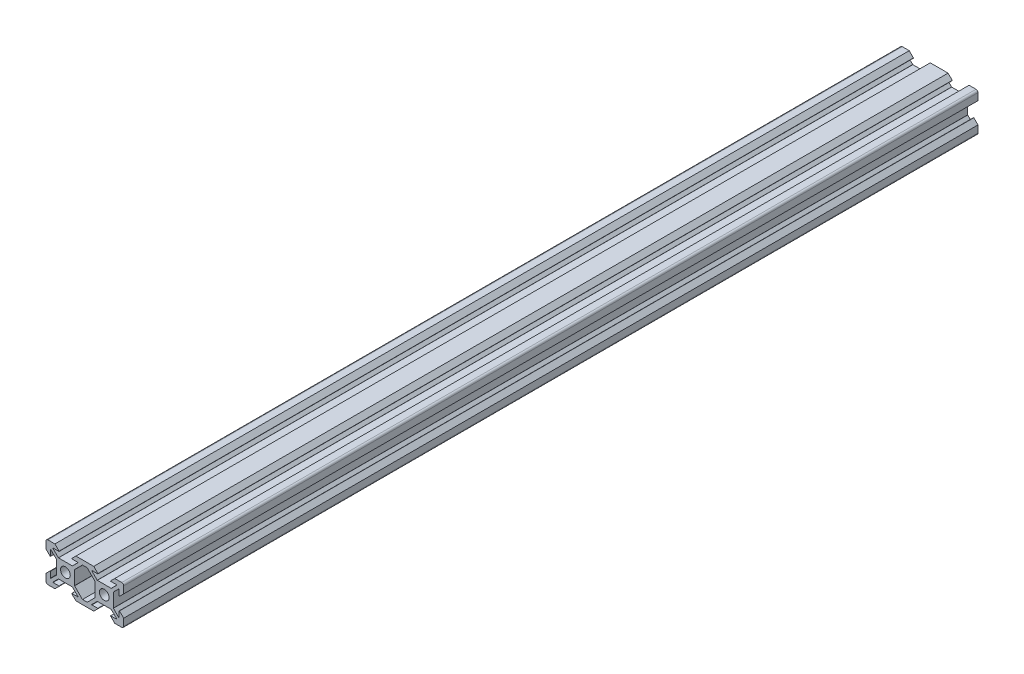
SolidWorks part; units mm, degrees
ref_plane "Alzado" through (0, 0, 0) normal (0, 0, 1) x (1, 0, 0)
ref_plane "Planta" through (0, 0, 0) normal (0, 1, 0) x (1, 0, 0)
ref_plane "Vista lateral" through (0, 0, 0) normal (1, 0, 0) x (0, 0, -1)
sketch "Croquis1" plane through (0, 0, 0) normal (0, 1, 0) x (1, 0, 0)
  line L0 (0, 220) -> (0, -220)
  dimension "D1" = 440
other "Miembro estructural1"
ref_plane "Plano1" through (0, 0, -220) normal (0, 0, 1) x (1, 0, 0)
sketch "Croquis4" plane through (0, 0, -220) normal (0, 0, 1) x (1, 0, 0)
  line L0 (0, 10) -> (0, 7.6897) construction
  line L1 (-19, -10) -> (-15.4103, -10)
  line L2 (-20, -9) -> (-20, -5.4103)
  line L3 (-19, 10) -> (-15.4103, 10)
  line L5 (20, 5.4103) -> (20, 9)
  line L6 (20, 5.4103) -> (17.8604, 3.2707)
  line L8 (17.6897, 3.3414) -> (17.6897, 6.3586)
  line L9 (-15.4103, 10) -> (-13.2707, 7.8604)
  line L10 (-13.3414, 7.6897) -> (-16.3586, 7.6897)
  line L11 (-16.4293, 7.519) -> (-13.6293, 4.719)
  line L12 (-13.5586, 4.6897) -> (-6.4414, 4.6897)
  line L13 (-3.5707, 7.519) -> (-6.3707, 4.719)
  line L14 (-6.6586, 7.6897) -> (-3.6414, 7.6897)
  line L15 (-4.5897, 10) -> (-6.7293, 7.8604)
  line L16 (-4.5897, 10) -> (4.5897, 10)
  line L17 (17.519, 6.4293) -> (14.719, 3.6293)
  line L18 (14.6897, -3.5586) -> (14.6897, 3.5586)
  line L19 (-2.481, 6.4293) -> (-5.281, 3.6293)
  line L20 (-5.3103, 3.5586) -> (-5.3103, -3.5586)
  line L21 (-2.481, -6.4293) -> (-5.281, -3.6293)
  line L22 (17.519, -6.4293) -> (14.719, -3.6293)
  line L23 (17.6897, -3.3414) -> (17.6897, -6.3586)
  line L24 (-4.5897, -10) -> (-6.7293, -7.8604)
  line L25 (-6.6586, -7.6897) -> (-3.6414, -7.6897)
  line L26 (-3.5707, -7.519) -> (-6.3707, -4.719)
  line L27 (-6.4414, -4.6897) -> (-13.5586, -4.6897)
  line L28 (-16.4293, -7.519) -> (-13.6293, -4.719)
  line L29 (-13.3414, -7.6897) -> (-16.3586, -7.6897)
  line L30 (-15.4103, -10) -> (-13.2707, -7.8604)
  line L31 (-20, -5.4103) -> (-17.8604, -3.2707)
  line L32 (-17.6897, -3.3414) -> (-17.6897, -6.3586)
  line L33 (-17.519, -6.4293) -> (-14.719, -3.6293)
  line L34 (-14.6897, -3.5586) -> (-14.6897, 3.5586)
  line L35 (-17.519, 6.4293) -> (-14.719, 3.6293)
  line L36 (-17.6897, 3.3414) -> (-17.6897, 6.3586)
  line L37 (-20, 5.4103) -> (-17.8604, 3.2707)
  line L38 (-20, 5.4103) -> (-20, 9)
  line L39 (-4.5897, -10) -> (4.5897, -10)
  line L40 (-2.3103, 3.3414) -> (-2.3103, 6.3586) [skipped]
  line L41 (0, 5.4103) -> (-2.1396, 3.2707) [skipped]
  line L42 (-2.3103, -3.3414) -> (-2.3103, -6.3586) [skipped]
  line L43 (0, -5.4103) -> (-2.1396, -3.2707) [skipped]
  line L44 (20, -5.4103) -> (17.8604, -3.2707)
  line L45 (15.4103, -10) -> (13.2707, -7.8604)
  line L46 (13.3414, -7.6897) -> (16.3586, -7.6897)
  line L47 (16.4293, -7.519) -> (13.6293, -4.719)
  line L48 (6.4414, -4.6897) -> (13.5586, -4.6897)
  line L49 (3.5707, -7.519) -> (6.3707, -4.719)
  line L50 (6.6586, -7.6897) -> (3.6414, -7.6897)
  line L51 (4.5897, -10) -> (6.7293, -7.8604)
  line L52 (2.481, -6.4293) -> (5.281, -3.6293)
  line L53 (5.3103, 3.5586) -> (5.3103, -3.5586)
  line L54 (2.481, 6.4293) -> (5.281, 3.6293)
  line L55 (4.5897, 10) -> (6.7293, 7.8604)
  line L56 (6.6586, 7.6897) -> (3.6414, 7.6897)
  line L57 (3.5707, 7.519) -> (6.3707, 4.719)
  line L58 (13.5586, 4.6897) -> (6.4414, 4.6897)
  line L59 (16.4293, 7.519) -> (13.6293, 4.719)
  line L60 (13.3414, 7.6897) -> (16.3586, 7.6897)
  line L61 (15.4103, 10) -> (13.2707, 7.8604)
  line L62 (19, 10) -> (15.4103, 10)
  line L63 (20, -9) -> (20, -5.4103)
  line L64 (19, -10) -> (15.4103, -10)
  line L65 (-3.6414, -7.6897) -> (3.6414, -7.6897) construction
  line L69 (-2.481, -6.4293) -> (-1.2206, -7.6897)
  line L70 (-1.2206, -7.6897) -> (1.2206, -7.6897)
  line L71 (2.481, -6.4293) -> (1.2206, -7.6897)
  line L72 (-2.481, 6.4293) -> (-1.2206, 7.6897)
  line L73 (-1.2206, 7.6897) -> (1.2206, 7.6897)
  line L74 (1.2206, 7.6897) -> (2.481, 6.4293)
  arc A0 (17.6897, 3.3414) -> (17.8604, 3.2707) centre (17.7897, 3.3414) ccw
  arc A1 (17.519, 6.4293) -> (17.6897, 6.3586) centre (17.5897, 6.3586) cw
  arc A2 (-19, -10) -> (-20, -9) centre (-19, -9) cw
  arc A3 (-20, 9) -> (-19, 10) centre (-19, 9) cw
  circle A4 centre (-10, 0) radius 2.5
  arc A5 (14.719, 3.6293) -> (14.6897, 3.5586) centre (14.7897, 3.5586) ccw
  arc A6 (-6.6586, 7.6897) -> (-6.7293, 7.8604) centre (-6.6586, 7.7897) cw
  arc A7 (-13.2707, 7.8604) -> (-13.3414, 7.6897) centre (-13.3414, 7.7897) cw
  arc A8 (-3.5707, 7.519) -> (-3.6414, 7.6897) centre (-3.6414, 7.5897) ccw
  arc A9 (-6.3707, 4.719) -> (-6.4414, 4.6897) centre (-6.4414, 4.7897) cw
  arc A10 (-13.6293, 4.719) -> (-13.5586, 4.6897) centre (-13.5586, 4.7897) ccw
  arc A11 (-16.3586, 7.6897) -> (-16.4293, 7.519) centre (-16.3586, 7.5897) ccw
  arc A12 (14.719, -3.6293) -> (14.6897, -3.5586) centre (14.7897, -3.5586) cw
  arc A13 (17.6897, -6.3586) -> (17.519, -6.4293) centre (17.5897, -6.3586) cw
  arc A14 (-5.281, 3.6293) -> (-5.3103, 3.5586) centre (-5.2103, 3.5586) ccw
  arc A15 (-5.281, -3.6293) -> (-5.3103, -3.5586) centre (-5.2103, -3.5586) cw
  arc A16 (17.8604, -3.2707) -> (17.6897, -3.3414) centre (17.7897, -3.3414) ccw
  arc A17 (13.3414, -7.6897) -> (13.2707, -7.8604) centre (13.3414, -7.7897) ccw
  arc A18 (-6.7293, -7.8604) -> (-6.6586, -7.6897) centre (-6.6586, -7.7897) cw
  arc A19 (-3.6414, -7.6897) -> (-3.5707, -7.519) centre (-3.6414, -7.5897) ccw
  arc A20 (-6.3707, -4.719) -> (-6.4414, -4.6897) centre (-6.4414, -4.7897) ccw
  arc A21 (-13.6293, -4.719) -> (-13.5586, -4.6897) centre (-13.5586, -4.7897) cw
  arc A22 (-16.4293, -7.519) -> (-16.3586, -7.6897) centre (-16.3586, -7.5897) ccw
  arc A23 (-13.3414, -7.6897) -> (-13.2707, -7.8604) centre (-13.3414, -7.7897) cw
  arc A24 (-17.8604, -3.2707) -> (-17.6897, -3.3414) centre (-17.7897, -3.3414) cw
  arc A25 (-17.6897, -6.3586) -> (-17.519, -6.4293) centre (-17.5897, -6.3586) ccw
  arc A26 (-14.719, -3.6293) -> (-14.6897, -3.5586) centre (-14.7897, -3.5586) ccw
  arc A27 (-14.719, 3.6293) -> (-14.6897, 3.5586) centre (-14.7897, 3.5586) cw
  arc A28 (-17.519, 6.4293) -> (-17.6897, 6.3586) centre (-17.5897, 6.3586) ccw
  arc A29 (-17.6897, 3.3414) -> (-17.8604, 3.2707) centre (-17.7897, 3.3414) cw
  arc A30 (-2.3103, 6.3586) -> (-2.481, 6.4293) centre (-2.4103, 6.3586) ccw [skipped]
  arc A31 (-2.1396, 3.2707) -> (-2.3103, 3.3414) centre (-2.2103, 3.3414) cw [skipped]
  arc A32 (-2.481, -6.4293) -> (-2.3103, -6.3586) centre (-2.4103, -6.3586) ccw [skipped]
  arc A33 (-2.3103, -3.3414) -> (-2.1396, -3.2707) centre (-2.2103, -3.3414) cw [skipped]
  arc A34 (16.4293, -7.519) -> (16.3586, -7.6897) centre (16.3586, -7.5897) cw
  arc A35 (13.6293, -4.719) -> (13.5586, -4.6897) centre (13.5586, -4.7897) ccw
  arc A36 (6.3707, -4.719) -> (6.4414, -4.6897) centre (6.4414, -4.7897) cw
  arc A37 (3.6414, -7.6897) -> (3.5707, -7.519) centre (3.6414, -7.5897) cw
  arc A38 (6.7293, -7.8604) -> (6.6586, -7.6897) centre (6.6586, -7.7897) ccw
  arc A39 (5.281, -3.6293) -> (5.3103, -3.5586) centre (5.2103, -3.5586) ccw
  arc A40 (5.281, 3.6293) -> (5.3103, 3.5586) centre (5.2103, 3.5586) cw
  arc A41 (16.3586, 7.6897) -> (16.4293, 7.519) centre (16.3586, 7.5897) cw
  arc A42 (13.6293, 4.719) -> (13.5586, 4.6897) centre (13.5586, 4.7897) cw
  arc A43 (6.3707, 4.719) -> (6.4414, 4.6897) centre (6.4414, 4.7897) ccw
  arc A44 (3.5707, 7.519) -> (3.6414, 7.6897) centre (3.6414, 7.5897) cw
  arc A45 (13.2707, 7.8604) -> (13.3414, 7.6897) centre (13.3414, 7.7897) ccw
  arc A46 (6.6586, 7.6897) -> (6.7293, 7.8604) centre (6.6586, 7.7897) ccw
  circle A47 centre (10, 0) radius 2.5
  arc A48 (20, 9) -> (19, 10) centre (19, 9) ccw
  arc A49 (19, -10) -> (20, -9) centre (19, -9) ccw
  point P0 (0, 0)
  point P2 (0, 0)
  point P34 (-10, 4.6897)
  point P39 (-6.9, 7.6897)
  point P42 (-13.1, 7.6897)
  point P45 (-3.4, 7.6897)
  point P48 (-6.4, 4.6897)
  point P51 (-13.6, 4.6897)
  point P54 (-16.6, 7.6897)
  point P118 (-10, 0)
  point P188 (16.6, 7.6897)
  point P189 (13.6, 4.6897)
  point P190 (6.4, 4.6897)
  point P191 (3.4, 7.6897)
  point P192 (13.1, 7.6897)
  point P193 (6.9, 7.6897)
  point P194 (10, 4.6897)
  point P200 (0, -7.6897)
  dimension "D5" = 5
  dimension "D10" = 0.1
  dimension "D11" = 0.1
  dimension "D7" = 3
  dimension "D8" = 3.5
  dimension "D9" = 45
  dimension "D12" = 4
